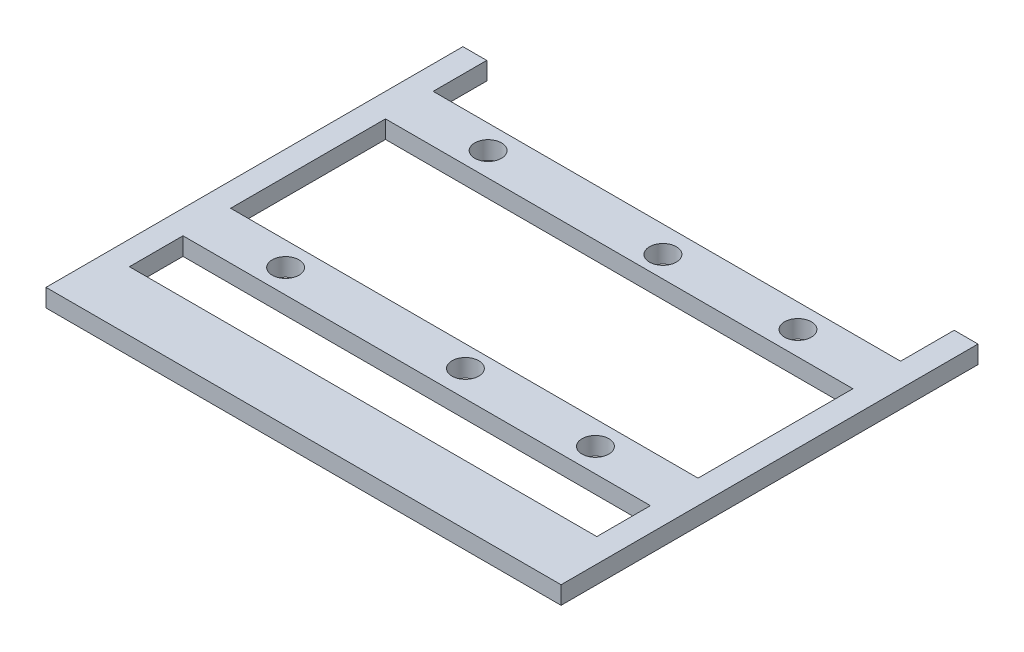
SolidWorks part; units mm, degrees
ref_plane "Front Plane" through (0, 0, 0) normal (0, 0, 1) x (1, 0, 0)
ref_plane "Top Plane" through (0, 0, 0) normal (0, 1, 0) x (1, 0, 0)
ref_plane "Right Plane" through (0, 0, 0) normal (1, 0, 0) x (0, 0, -1)
sketch "Sketch2" plane through (0, 0, 0) normal (0, 1, 0) x (1, 0, 0)
  point P4 (0, 0)
sketch "Sketch3" plane through (0, 0, 0) normal (0, 1, 0) x (1, 0, 0)
  line L0 (-43.2391, 0) -> (43.2391, 0) construction
  line L1 (-39.2391, -13) -> (-39.2391, 13)
  line L2 (-39.2391, 13) -> (39.2391, 13)
  line L3 (39.2391, 13) -> (39.2391, -13)
  line L4 (-43.2391, -30) -> (-43.2391, 30)
  line L5 (-43.2391, 30) -> (-39.2391, 30)
  line L6 (-39.2391, 30) -> (-39.2391, 21)
  line L7 (-39.2391, 21) -> (39.2391, 21)
  line L8 (39.2391, 21) -> (39.2391, 30)
  line L9 (39.2391, 30) -> (43.2391, 30)
  line L10 (43.2391, 30) -> (43.2391, -30)
  line L11 (39.2391, -30) -> (43.2391, -30)
  line L12 (39.2391, -21) -> (39.2391, -30)
  line L13 (-39.2391, -21) -> (39.2391, -21)
  line L14 (-39.2391, -30) -> (-39.2391, -21)
  line L15 (-43.2391, -30) -> (-39.2391, -30)
  line L16 (-39.2391, -13) -> (39.2391, -13)
  circle A0 centre (-26.0091, 17) radius 2.25
  circle A1 centre (3.7609, 16.5788) radius 2.25
  circle A2 centre (26.0091, 17) radius 2.25
  circle A3 centre (26.0091, -17) radius 2.25
  circle A4 centre (3.7609, -16.5788) radius 2.25
  circle A5 centre (-26.0091, -17) radius 2.25
  point P4 (0, 0)
  point P21 (0, 0)
  point P22 (-39.2391, 25.5)
  point P36 (39.2391, 0)
  point P37 (-39.2391, 0)
  dimension "D10" = 4.5
  dimension "D11" = 4.5
  dimension "D12" = 4.5
  dimension "D1" = 4
  dimension "D2" = 4
  dimension "D3" = 30
  dimension "D4" = 30
  dimension "D5" = 4
  dimension "D6" = 4
  dimension "D7" = 17
  dimension "D8" = 17
  dimension "D9" = 17
  dimension "D13" = 8
  dimension "D14" = 4
  dimension "D15" = 13.23
  dimension "D16" = 43
  dimension "D17" = 13.23
extrude "Boss-Extrude1" add sketch "Sketch3" along normal blind 3
sketch "Sketch4" plane through (0, 0, 30) normal (0, 0, 1) x (1, 0, 0)
  line L1 (-43.2391, 0) -> (43.2391, 0)
  line L2 (-43.2391, 0) -> (-43.2391, 3)
  line L3 (-43.2391, 3) -> (43.2391, 3)
  line L4 (43.2391, 0) -> (43.2391, 3)
extrude "Boss-Extrude2" add sketch "Sketch4" along normal blind 10
